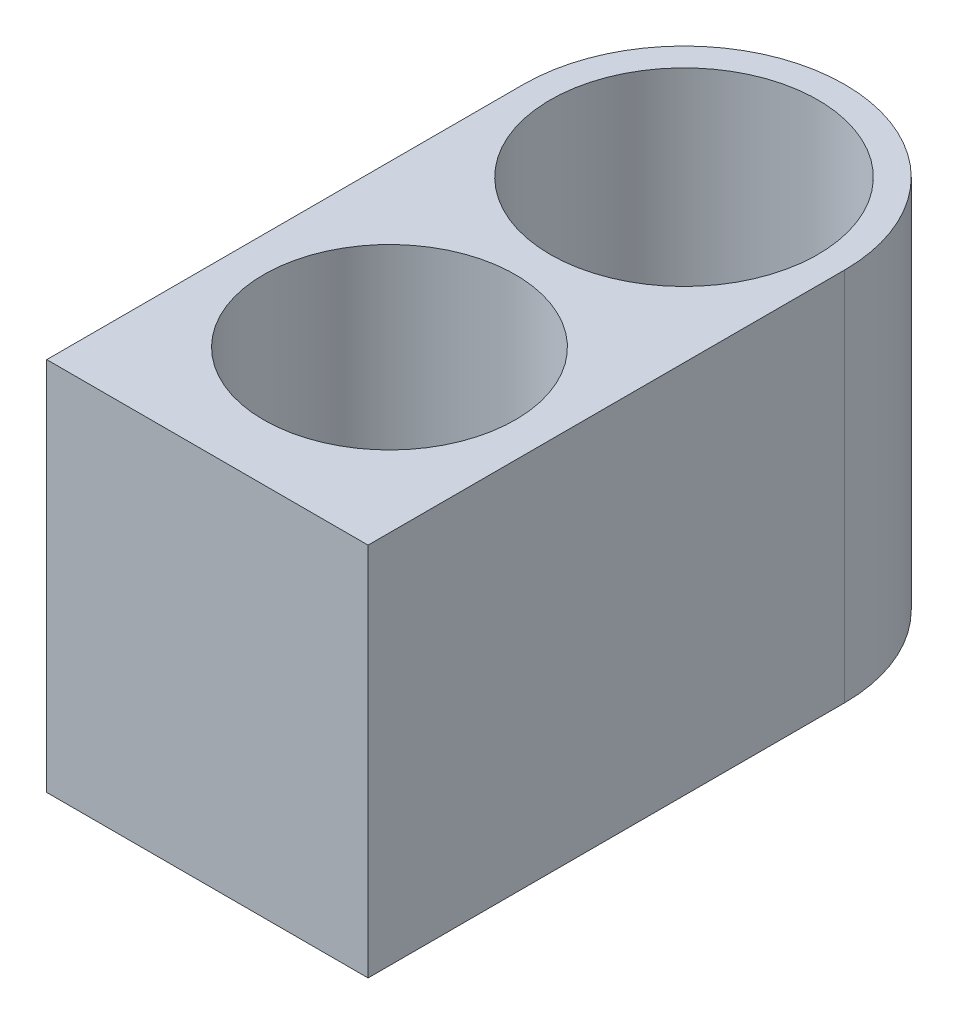
SolidWorks part; units mm, degrees
ref_plane "Front Plane" through (0, 0, 0) normal (0, 0, 1) x (1, 0, 0)
ref_plane "Top Plane" through (0, 0, 0) normal (0, 1, 0) x (1, 0, 0)
ref_plane "Right Plane" through (0, 0, 0) normal (1, 0, 0) x (0, 0, -1)
sketch "Sketch4" plane through (0, 0, 0) normal (0, 1, 0) x (1, 0, 0)
  line L1 (-3, -6) -> (3, -6)
  line L2 (-3, -6) -> (-3, 6)
  line L3 (-3, 6) -> (3, 6)
  line L4 (3, -6) -> (3, 6)
  line L5 (-3, -6) -> (3, 6) construction
  line L6 (-3, 6) -> (3, -6) construction
  point P0 (0, 0)
  dimension "D1" = 12
  dimension "D2" = 6
extrude "Boss-Extrude2" add sketch "Sketch4" along normal blind 7
sketch "Sketch5" plane through (0, 7, 0) normal (0, 1, 0) x (1, 0, 0)
  line L0 (-3, -6) -> (3, -6) construction
  circle A0 centre (0, -2.6) radius 2.35
  circle A1 centre (0, 2.9) radius 2.5
  dimension "D1" = 4.7
  dimension "D2" = 5
  dimension "D3" = 3.4
  dimension "D4" = 5.5
extrude "Cut-Extrude2" cut sketch "Sketch5" against normal through all
sketch "Sketch7" plane through (0, 7, 0) normal (0, 1, 0) x (1, 0, 0)
  line L0 (3, -6) -> (3, 6) construction
  line L1 (-3, 6) -> (-3, -6) construction
  line L2 (-3, 2.9) -> (-3, 6)
  line L3 (-3, 6) -> (3, 6)
  line L4 (3, 6) -> (3, 2.9)
  arc A0 (3, 2.9) -> (-3, 2.9) centre (0, 2.9) ccw
extrude "Cut-Extrude3" cut sketch "Sketch7" against normal through all
